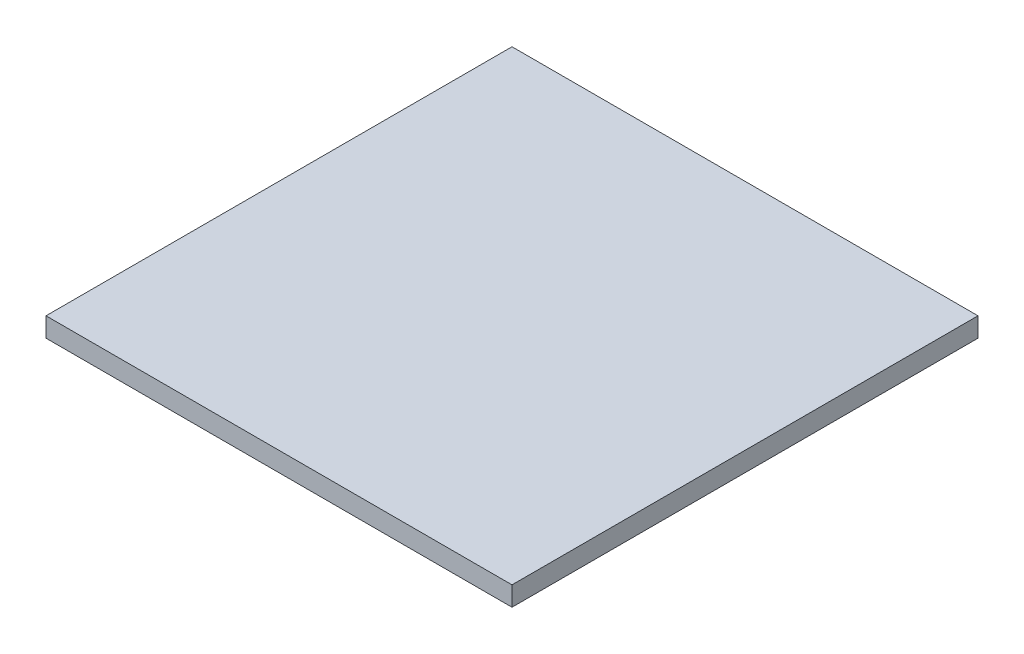
SolidWorks part; units mm, degrees
ref_plane "Front Plane" through (0, 0, 0) normal (0, 0, 1) x (1, 0, 0)
ref_plane "Top Plane" through (0, 0, 0) normal (0, 1, 0) x (1, 0, 0)
ref_plane "Right Plane" through (0, 0, 0) normal (1, 0, 0) x (0, 0, -1)
sketch "Sketch1" plane through (0, 0, 0) normal (0, 1, 0) x (1, 0, 0)
  line L1 (-76.2, -76.2) -> (76.2, -76.2)
  line L2 (-76.2, -76.2) -> (-76.2, 76.2)
  line L3 (-76.2, 76.2) -> (76.2, 76.2)
  line L4 (76.2, -76.2) -> (76.2, 76.2)
  line L5 (-76.2, -76.2) -> (76.2, 76.2) construction
  line L6 (-76.2, 76.2) -> (76.2, -76.2) construction
  point P0 (0, 0)
  dimension "D1" = 76.2
  dimension "D2" = 76.2
extrude "Boss-Extrude1" add sketch "Sketch1" along normal blind 6.35
